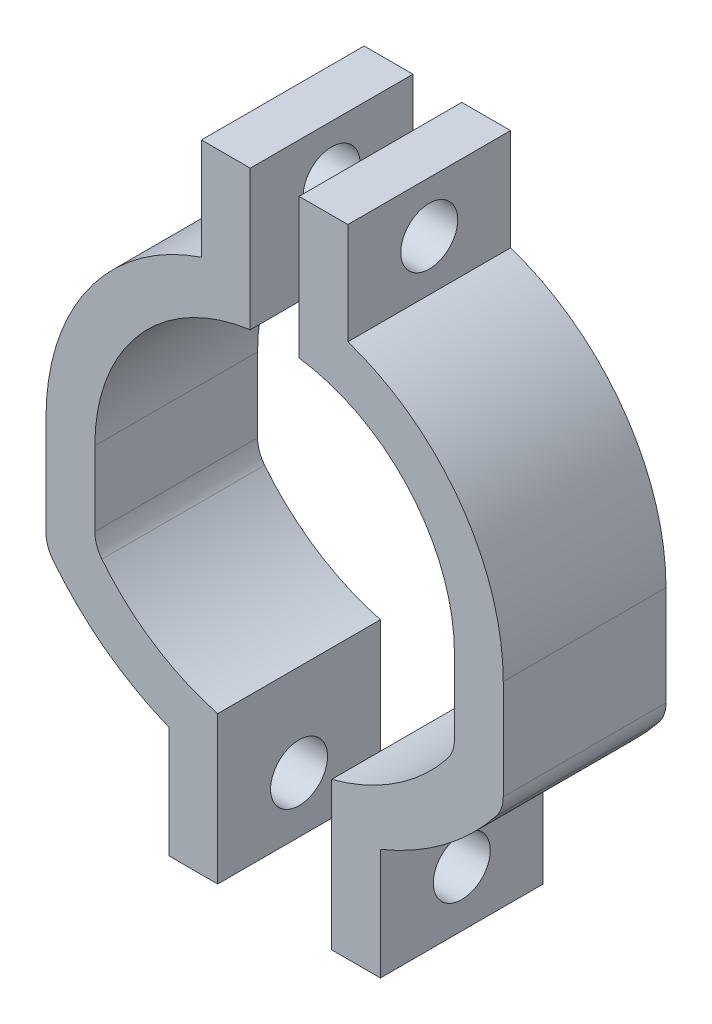
SolidWorks part; units mm, degrees
ref_plane "Front Plane" through (0, 0, 0) normal (0, 0, 1) x (1, 0, 0)
ref_plane "Top Plane" through (0, 0, 0) normal (0, 1, 0) x (1, 0, 0)
ref_plane "Right Plane" through (0, 0, 0) normal (1, 0, 0) x (0, 0, -1)
sketch "Sketch1" plane through (0, 0, 0) normal (0, 0, 1) x (1, 0, 0)
  line L0 (0, -14.05) -> (0, -19.55) construction
  line L2 (-3.5, -19.55) -> (-3.5, -13.6071)
  line L3 (3.5, -19.55) -> (3.5, -13.6071)
  line L6 (-14.05, 0) -> (14.05, 0) construction
  line L7 (-11.05, 0) -> (-11.05, -4.5734)
  line L8 (-14.05, 0) -> (-14.05, -6.1317)
  line L9 (11.05, 0) -> (11.05, -4.5734)
  line L10 (14.05, 0) -> (14.05, -6.1317)
  line L11 (-3.5, -10.4811) -> (-3.5, -13.6071)
  line L12 (3.5, -10.4811) -> (3.5, -13.6071)
  line L13 (-6.5, -19.55) -> (-3.5, -19.55)
  line L14 (-6.5, -19.55) -> (-6.5, -12.7011)
  line L15 (6.5, -19.55) -> (6.5, -12.7011)
  line L16 (3.5, -19.55) -> (6.5, -19.55)
  line L17 (-1.5, 19.55) -> (-4.5, 19.55)
  line L19 (-1.5, 19.55) -> (-1.5, 10.9477)
  line L20 (1.5, 19.55) -> (1.5, 10.9477)
  line L21 (1.5, 19.55) -> (4.5, 19.55)
  line L22 (-4.5, 19.55) -> (-4.5, 13.3099)
  line L23 (4.5, 19.55) -> (4.5, 13.3099)
  arc A1 (14.05, 0) -> (4.5, 13.3099) centre (0, 0) ccw
  arc A2 (11.05, 0) -> (1.5, 10.9477) centre (0, 0) ccw
  arc A4 (-10.6156, -5.8179) -> (-3.5, -10.4811) centre (0, 2.6203) ccw
  arc A5 (-4.5, 13.3099) -> (-14.05, 0) centre (0, 0) ccw
  arc A6 (-10.6156, -5.8179) -> (-11.05, -4.5734) centre (-9.05, -4.5734) cw
  arc A7 (-13.6185, -7.3726) -> (-6.5, -12.7011) centre (0, 3.4018) ccw
  arc A8 (-13.6185, -7.3726) -> (-14.05, -6.1317) centre (-12.05, -6.1317) cw
  arc A9 (10.6156, -5.8179) -> (3.5, -10.4811) centre (0, 2.6203) cw
  arc A10 (13.6185, -7.3726) -> (6.5, -12.7011) centre (0, 3.4018) cw
  arc A11 (10.6156, -5.8179) -> (11.05, -4.5734) centre (9.05, -4.5734) ccw
  arc A12 (13.6185, -7.3726) -> (14.05, -6.1317) centre (12.05, -6.1317) ccw
  arc A13 (-1.5, 10.9477) -> (-11.05, 0) centre (0, 0) ccw
  point P9 (0, -19.55)
  point P34 (0, -19.55)
  point P39 (0, 19.55)
  point P42 (0, 0)
  point P44 (0, 0)
  dimension "D1" = 2
  dimension "D2" = 2
extrude "Boss-Extrude1" add sketch "Sketch1" along normal blind 10
sketch "Sketch2" plane through (6.5, 0, 0) normal (1, 0, 0) x (0, 0, -1)
  circle A0 centre (-5, -16.1255) radius 1.75
  dimension "D1" = 3.5
sketch "Sketch3" plane through (4.5, 0, 0) normal (1, 0, 0) x (0, 0, -1)
  circle A0 centre (-5, 16.4299) radius 1.75
  dimension "D1" = 3.5
extrude "Cut-Extrude1" cut sketch "Sketch3" against normal blind 9
extrude "Cut-Extrude2" cut sketch "Sketch2" against normal blind 13
